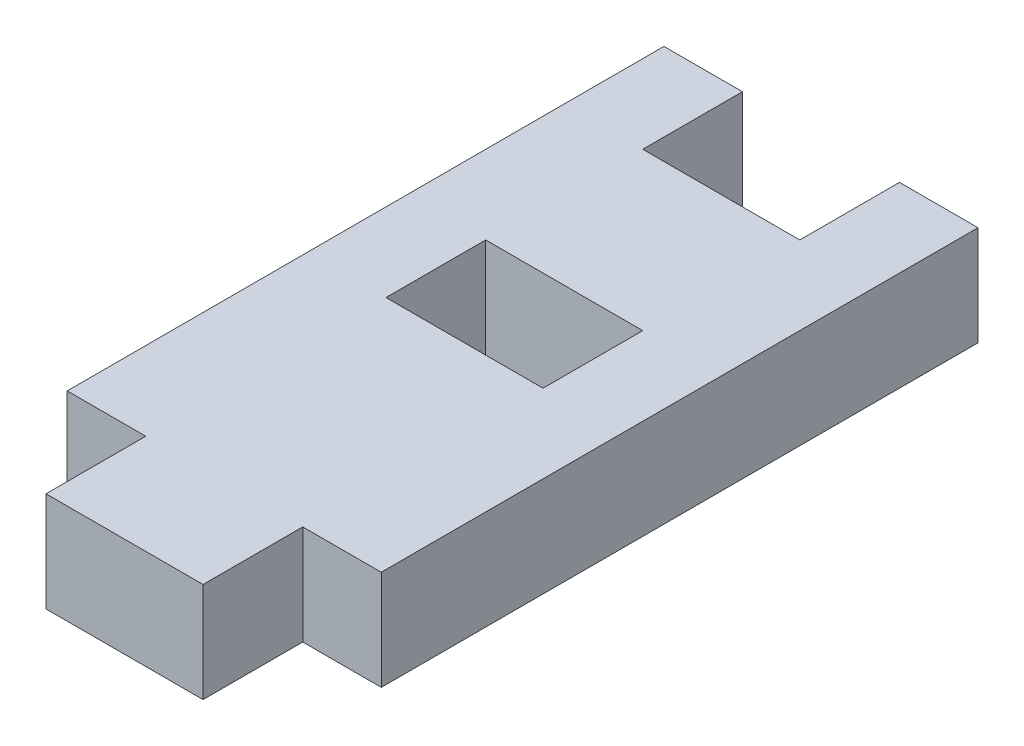
SolidWorks part; units mm, degrees
material "Balsa"
ref_plane "Front Plane" through (0, 0, 0) normal (0, 0, 1) x (1, 0, 0)
ref_plane "Top Plane" through (0, 0, 0) normal (0, 1, 0) x (1, 0, 0)
ref_plane "Right Plane" through (0, 0, 0) normal (1, 0, 0) x (0, 0, -1)
sketch "Sketch1" plane through (0, 0, 0) normal (0, 1, 0) x (1, 0, 0)
  line L0 (0, 0) -> (5, 0)
  line L1 (5, 0) -> (5, -6.35)
  line L2 (5, -6.35) -> (15, -6.35)
  line L3 (15, -6.35) -> (15, 0)
  line L4 (15, 0) -> (20, 0)
  line L5 (20, 0) -> (20, 38)
  line L6 (20, 38) -> (15, 38)
  line L7 (15, 38) -> (15, 31.65)
  line L8 (15, 31.65) -> (5, 31.65)
  line L9 (5, 31.65) -> (5, 38)
  line L10 (5, 38) -> (0, 38)
  line L11 (0, 38) -> (0, 0)
  line L12 (5, 21.65) -> (5, 15.3)
  line L13 (5, 15.3) -> (15, 15.3)
  line L14 (15, 15.3) -> (15, 21.65)
  line L15 (15, 21.65) -> (5, 21.65)
  dimension "D1" = 10
  dimension "D2" = 6.35
  dimension "D3" = 38
  dimension "D4" = 20
  dimension "D5" = 10
extrude "Boss-Extrude1" add sketch "Sketch1" along normal blind 6.35
